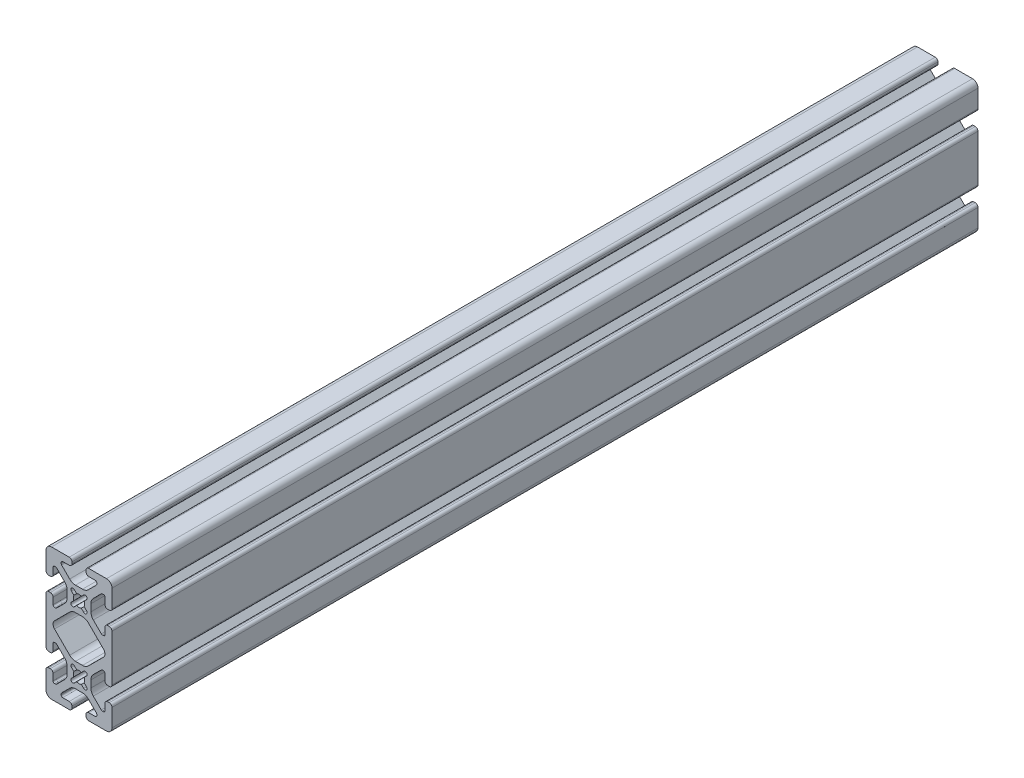
SolidWorks part; units mm, degrees
material "6061-T6 (SS)"
ref_plane "Front Plane" through (0, 0, 0) normal (0, 0, 1) x (1, 0, 0)
ref_plane "Top Plane" through (0, 0, 0) normal (0, 1, 0) x (1, 0, 0)
ref_plane "Right Plane" through (0, 0, 0) normal (1, 0, 0) x (0, 0, -1)
sketch "Sketch1" plane through (0, 0, 0) normal (0, 0, 1) x (1, 0, 0)
  line L0 (4.2456, -16.4102) -> (2.9729, -17.6936)
  line L1 (2.9729, -20.4064) -> (4.3433, -21.7769)
  line L2 (2.7269, -23.3933) -> (1.3564, -22.0229)
  line L3 (-1.3564, -22.0229) -> (-2.7269, -23.3933)
  line L4 (-4.3433, -21.7769) -> (-2.9729, -20.4064)
  line L5 (-2.9729, -17.6936) -> (-4.3433, -16.3231)
  line L6 (-2.7269, -14.7067) -> (-1.3564, -16.0771)
  line L7 (1.3564, -16.0771) -> (2.6398, -14.8044)
  line L8 (14.1109, -2.0655) -> (5.3872, -10.7892)
  line L9 (2.0285, -12.1803) -> (-2.0285, -12.1803)
  line L10 (-5.3872, -10.7892) -> (-14.1109, -2.0655)
  line L11 (-14.1109, 2.0655) -> (-5.3872, 10.7892)
  line L12 (-2.0285, 12.1803) -> (2.0285, 12.1803)
  line L13 (5.3872, 10.7892) -> (14.1109, 2.0655)
  line L14 (4.2456, 21.6898) -> (2.9729, 20.4064)
  line L15 (2.9729, 17.6936) -> (4.3433, 16.3231)
  line L16 (2.7269, 14.7067) -> (1.3564, 16.0771)
  line L17 (-1.3564, 16.0771) -> (-2.7269, 14.7067)
  line L18 (-4.3433, 16.3231) -> (-2.9729, 17.6936)
  line L19 (-2.9729, 20.4064) -> (-4.3433, 21.7769)
  line L20 (-2.7269, 23.3933) -> (-1.3564, 22.0229)
  line L21 (1.3564, 22.0229) -> (2.6398, 23.2956)
  line L22 (16.5608, 23.114) -> (17.4752, 23.114)
  line L23 (19.05, 24.6888) -> (19.05, 34.925)
  line L24 (15.875, 38.1) -> (5.6388, 38.1)
  line L25 (4.064, 36.5252) -> (4.064, 35.6108)
  line L26 (5.6388, 34.036) -> (9.398, 34.036)
  line L27 (10.287, 33.147) -> (10.287, 32.5789)
  line L28 (10.0266, 31.9503) -> (5.3872, 27.3108)
  line L29 (2.0285, 25.9197) -> (-2.0285, 25.9197)
  line L30 (-5.3872, 27.3108) -> (-10.0266, 31.9503)
  line L31 (-10.287, 32.5789) -> (-10.287, 33.147)
  line L32 (-9.398, 34.036) -> (-5.6388, 34.036)
  line L33 (-4.064, 35.6108) -> (-4.064, 36.5252)
  line L34 (-5.6388, 38.1) -> (-15.875, 38.1)
  line L35 (-19.05, 34.925) -> (-19.05, 24.6888)
  line L36 (-17.4752, 23.114) -> (-16.5608, 23.114)
  line L37 (-14.986, 24.6888) -> (-14.986, 28.448)
  line L38 (-14.097, 29.337) -> (-13.5289, 29.337)
  line L39 (-12.9003, 29.0766) -> (-8.2608, 24.4372)
  line L40 (-6.8697, 21.0785) -> (-6.8697, 17.0215)
  line L41 (-8.2608, 13.6628) -> (-12.9003, 9.0234)
  line L42 (-13.5289, 8.763) -> (-14.097, 8.763)
  line L43 (-14.986, 9.652) -> (-14.986, 13.4112)
  line L44 (-16.5608, 14.986) -> (-17.4752, 14.986)
  line L45 (-19.05, 13.4112) -> (-19.05, -13.4112)
  line L46 (-17.4752, -14.986) -> (-16.5608, -14.986)
  line L47 (-14.986, -13.4112) -> (-14.986, -9.652)
  line L48 (-14.097, -8.763) -> (-13.5289, -8.763)
  line L49 (-12.9003, -9.0234) -> (-8.2608, -13.6628)
  line L50 (-6.8697, -17.0215) -> (-6.8697, -21.0785)
  line L51 (-8.2608, -24.4372) -> (-12.9003, -29.0766)
  line L52 (-13.5289, -29.337) -> (-14.097, -29.337)
  line L53 (-14.986, -28.448) -> (-14.986, -24.6888)
  line L54 (-16.5608, -23.114) -> (-17.4752, -23.114)
  line L55 (-19.05, -24.6888) -> (-19.05, -34.925)
  line L56 (-15.875, -38.1) -> (-5.6388, -38.1)
  line L57 (-4.064, -36.5252) -> (-4.064, -35.6108)
  line L58 (-5.6388, -34.036) -> (-9.398, -34.036)
  line L59 (-10.287, -33.147) -> (-10.287, -32.5789)
  line L60 (-10.0266, -31.9503) -> (-5.3872, -27.3108)
  line L61 (-2.0285, -25.9197) -> (2.0285, -25.9197)
  line L62 (5.3872, -27.3108) -> (10.0266, -31.9503)
  line L63 (10.287, -32.5789) -> (10.287, -33.147)
  line L64 (9.398, -34.036) -> (5.6388, -34.036)
  line L65 (4.064, -35.6108) -> (4.064, -36.5252)
  line L66 (5.6388, -38.1) -> (15.875, -38.1)
  line L67 (19.05, -34.925) -> (19.05, -24.6888)
  line L68 (17.4752, -23.114) -> (16.5608, -23.114)
  line L69 (14.986, -24.6888) -> (14.986, -28.448)
  line L70 (14.097, -29.337) -> (13.5289, -29.337)
  line L71 (12.9003, -29.0766) -> (8.2608, -24.4372)
  line L72 (6.8697, -21.0785) -> (6.8697, -17.0215)
  line L73 (8.2608, -13.6628) -> (12.9003, -9.0234)
  line L74 (13.5289, -8.763) -> (14.097, -8.763)
  line L75 (14.986, -9.652) -> (14.986, -13.4112)
  line L76 (16.5608, -14.986) -> (17.4752, -14.986)
  line L77 (19.05, -13.4112) -> (19.05, 13.4112)
  line L78 (17.4752, 14.986) -> (16.5608, 14.986)
  line L79 (14.986, 13.4112) -> (14.986, 9.652)
  line L80 (14.097, 8.763) -> (13.5289, 8.763)
  line L81 (12.9003, 9.0234) -> (8.2608, 13.6628)
  line L82 (6.8697, 17.0215) -> (6.8697, 21.0785)
  line L83 (8.2608, 24.4372) -> (12.9003, 29.0766)
  line L84 (13.5289, 29.337) -> (14.097, 29.337)
  line L85 (14.986, 28.448) -> (14.986, 24.6888)
  arc A0 (4.2456, -16.4102) -> (2.6398, -14.8044) centre (3.5351, -15.5149) ccw
  arc A1 (2.9729, -20.4064) -> (2.9729, -17.6936) centre (0, -19.05) ccw
  arc A2 (2.7269, -23.3933) -> (4.3433, -21.7769) centre (3.5351, -22.5851) ccw
  arc A3 (-1.3564, -22.0229) -> (1.3564, -22.0229) centre (0, -19.05) ccw
  arc A4 (-4.3433, -21.7769) -> (-2.7269, -23.3933) centre (-3.5351, -22.5851) ccw
  arc A5 (-2.9729, -17.6936) -> (-2.9729, -20.4064) centre (0, -19.05) ccw
  arc A6 (-2.7269, -14.7067) -> (-4.3433, -16.3231) centre (-3.5351, -15.5149) ccw
  arc A7 (1.3564, -16.0771) -> (-1.3564, -16.0771) centre (0, -19.05) ccw
  arc A8 (14.1109, -2.0655) -> (14.1109, 2.0655) centre (12.0454, 0) ccw
  arc A9 (2.0285, -12.1803) -> (5.3872, -10.7892) centre (2.0285, -7.4305) ccw
  arc A10 (-5.3872, -10.7892) -> (-2.0285, -12.1803) centre (-2.0285, -7.4305) ccw
  arc A11 (-14.1109, 2.0655) -> (-14.1109, -2.0655) centre (-12.0454, 0) ccw
  arc A12 (-2.0285, 12.1803) -> (-5.3872, 10.7892) centre (-2.0285, 7.4305) ccw
  arc A13 (5.3872, 10.7892) -> (2.0285, 12.1803) centre (2.0285, 7.4305) ccw
  arc A14 (4.2456, 21.6898) -> (2.6398, 23.2956) centre (3.5351, 22.5851) ccw
  arc A15 (2.9729, 17.6936) -> (2.9729, 20.4064) centre (0, 19.05) ccw
  arc A16 (2.7269, 14.7067) -> (4.3433, 16.3231) centre (3.5351, 15.5149) ccw
  arc A17 (-1.3564, 16.0771) -> (1.3564, 16.0771) centre (0, 19.05) ccw
  arc A18 (-4.3433, 16.3231) -> (-2.7269, 14.7067) centre (-3.5351, 15.5149) ccw
  arc A19 (-2.9729, 20.4064) -> (-2.9729, 17.6936) centre (0, 19.05) ccw
  arc A20 (-2.7269, 23.3933) -> (-4.3433, 21.7769) centre (-3.5351, 22.5851) ccw
  arc A21 (1.3564, 22.0229) -> (-1.3564, 22.0229) centre (0, 19.05) ccw
  arc A22 (14.986, 24.6888) -> (16.5608, 23.114) centre (16.5608, 24.6888) ccw
  arc A23 (17.4752, 23.114) -> (19.05, 24.6888) centre (17.4752, 24.6888) ccw
  arc A24 (19.05, 34.925) -> (15.875, 38.1) centre (15.875, 34.925) ccw
  arc A25 (5.6388, 38.1) -> (4.064, 36.5252) centre (5.6388, 36.5252) ccw
  arc A26 (4.064, 35.6108) -> (5.6388, 34.036) centre (5.6388, 35.6108) ccw
  arc A27 (10.287, 33.147) -> (9.398, 34.036) centre (9.398, 33.147) ccw
  arc A28 (10.0266, 31.9503) -> (10.287, 32.5789) centre (9.398, 32.5789) ccw
  arc A29 (2.0285, 25.9197) -> (5.3872, 27.3108) centre (2.0285, 30.6695) ccw
  arc A30 (-5.3872, 27.3108) -> (-2.0285, 25.9197) centre (-2.0285, 30.6695) ccw
  arc A31 (-10.287, 32.5789) -> (-10.0266, 31.9503) centre (-9.398, 32.5789) ccw
  arc A32 (-9.398, 34.036) -> (-10.287, 33.147) centre (-9.398, 33.147) ccw
  arc A33 (-5.6388, 34.036) -> (-4.064, 35.6108) centre (-5.6388, 35.6108) ccw
  arc A34 (-4.064, 36.5252) -> (-5.6388, 38.1) centre (-5.6388, 36.5252) ccw
  arc A35 (-15.875, 38.1) -> (-19.05, 34.925) centre (-15.875, 34.925) ccw
  arc A36 (-19.05, 24.6888) -> (-17.4752, 23.114) centre (-17.4752, 24.6888) ccw
  arc A37 (-16.5608, 23.114) -> (-14.986, 24.6888) centre (-16.5608, 24.6888) ccw
  arc A38 (-14.097, 29.337) -> (-14.986, 28.448) centre (-14.097, 28.448) ccw
  arc A39 (-12.9003, 29.0766) -> (-13.5289, 29.337) centre (-13.5289, 28.448) ccw
  arc A40 (-6.8697, 21.0785) -> (-8.2608, 24.4372) centre (-11.6195, 21.0785) ccw
  arc A41 (-8.2608, 13.6628) -> (-6.8697, 17.0215) centre (-11.6195, 17.0215) ccw
  arc A42 (-13.5289, 8.763) -> (-12.9003, 9.0234) centre (-13.5289, 9.652) ccw
  arc A43 (-14.986, 9.652) -> (-14.097, 8.763) centre (-14.097, 9.652) ccw
  arc A44 (-14.986, 13.4112) -> (-16.5608, 14.986) centre (-16.5608, 13.4112) ccw
  arc A45 (-17.4752, 14.986) -> (-19.05, 13.4112) centre (-17.4752, 13.4112) ccw
  arc A46 (-19.05, -13.4112) -> (-17.4752, -14.986) centre (-17.4752, -13.4112) ccw
  arc A47 (-16.5608, -14.986) -> (-14.986, -13.4112) centre (-16.5608, -13.4112) ccw
  arc A48 (-14.097, -8.763) -> (-14.986, -9.652) centre (-14.097, -9.652) ccw
  arc A49 (-12.9003, -9.0234) -> (-13.5289, -8.763) centre (-13.5289, -9.652) ccw
  arc A50 (-6.8697, -17.0215) -> (-8.2608, -13.6628) centre (-11.6195, -17.0215) ccw
  arc A51 (-8.2608, -24.4372) -> (-6.8697, -21.0785) centre (-11.6195, -21.0785) ccw
  arc A52 (-13.5289, -29.337) -> (-12.9003, -29.0766) centre (-13.5289, -28.448) ccw
  arc A53 (-14.986, -28.448) -> (-14.097, -29.337) centre (-14.097, -28.448) ccw
  arc A54 (-14.986, -24.6888) -> (-16.5608, -23.114) centre (-16.5608, -24.6888) ccw
  arc A55 (-17.4752, -23.114) -> (-19.05, -24.6888) centre (-17.4752, -24.6888) ccw
  arc A56 (-19.05, -34.925) -> (-15.875, -38.1) centre (-15.875, -34.925) ccw
  arc A57 (-5.6388, -38.1) -> (-4.064, -36.5252) centre (-5.6388, -36.5252) ccw
  arc A58 (-4.064, -35.6108) -> (-5.6388, -34.036) centre (-5.6388, -35.6108) ccw
  arc A59 (-10.287, -33.147) -> (-9.398, -34.036) centre (-9.398, -33.147) ccw
  arc A60 (-10.0266, -31.9503) -> (-10.287, -32.5789) centre (-9.398, -32.5789) ccw
  arc A61 (-2.0285, -25.9197) -> (-5.3872, -27.3108) centre (-2.0285, -30.6695) ccw
  arc A62 (5.3872, -27.3108) -> (2.0285, -25.9197) centre (2.0285, -30.6695) ccw
  arc A63 (10.287, -32.5789) -> (10.0266, -31.9503) centre (9.398, -32.5789) ccw
  arc A64 (9.398, -34.036) -> (10.287, -33.147) centre (9.398, -33.147) ccw
  arc A65 (5.6388, -34.036) -> (4.064, -35.6108) centre (5.6388, -35.6108) ccw
  arc A66 (4.064, -36.5252) -> (5.6388, -38.1) centre (5.6388, -36.5252) ccw
  arc A67 (15.875, -38.1) -> (19.05, -34.925) centre (15.875, -34.925) ccw
  arc A68 (19.05, -24.6888) -> (17.4752, -23.114) centre (17.4752, -24.6888) ccw
  arc A69 (16.5608, -23.114) -> (14.986, -24.6888) centre (16.5608, -24.6888) ccw
  arc A70 (14.097, -29.337) -> (14.986, -28.448) centre (14.097, -28.448) ccw
  arc A71 (12.9003, -29.0766) -> (13.5289, -29.337) centre (13.5289, -28.448) ccw
  arc A72 (6.8697, -21.0785) -> (8.2608, -24.4372) centre (11.6195, -21.0785) ccw
  arc A73 (8.2608, -13.6628) -> (6.8697, -17.0215) centre (11.6195, -17.0215) ccw
  arc A74 (13.5289, -8.763) -> (12.9003, -9.0234) centre (13.5289, -9.652) ccw
  arc A75 (14.986, -9.652) -> (14.097, -8.763) centre (14.097, -9.652) ccw
  arc A76 (14.986, -13.4112) -> (16.5608, -14.986) centre (16.5608, -13.4112) ccw
  arc A77 (17.4752, -14.986) -> (19.05, -13.4112) centre (17.4752, -13.4112) ccw
  arc A78 (19.05, 13.4112) -> (17.4752, 14.986) centre (17.4752, 13.4112) ccw
  arc A79 (16.5608, 14.986) -> (14.986, 13.4112) centre (16.5608, 13.4112) ccw
  arc A80 (14.097, 8.763) -> (14.986, 9.652) centre (14.097, 9.652) ccw
  arc A81 (12.9003, 9.0234) -> (13.5289, 8.763) centre (13.5289, 9.652) ccw
  arc A82 (6.8697, 17.0215) -> (8.2608, 13.6628) centre (11.6195, 17.0215) ccw
  arc A83 (8.2608, 24.4372) -> (6.8697, 21.0785) centre (11.6195, 21.0785) ccw
  arc A84 (13.5289, 29.337) -> (12.9003, 29.0766) centre (13.5289, 28.448) ccw
  arc A85 (14.986, 28.448) -> (14.097, 29.337) centre (14.097, 28.448) ccw
extrude "Extrude1" add sketch "Sketch1" against normal blind 500
